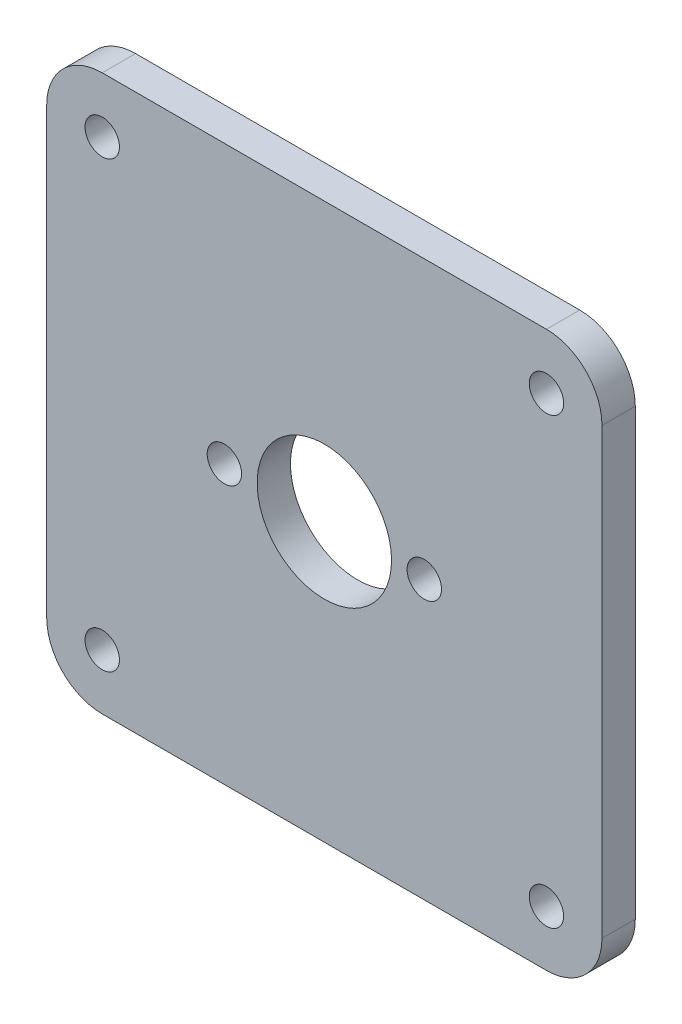
SolidWorks part; units mm, degrees
ref_plane "正面" through (0, 0, 0) normal (0, 0, 1) x (1, 0, 0)
ref_plane "平面" through (0, 0, 0) normal (0, 1, 0) x (1, 0, 0)
ref_plane "右側面" through (0, 0, 0) normal (1, 0, 0) x (0, 0, -1)
sketch "ｽｹｯﾁ1" plane through (0, 0, 0) normal (0, 0, 1) x (1, 0, 0)
  line L0 (0, 25) -> (0, -25) construction
  line L1 (-25, 25) -> (25, 25)
  line L2 (-25, 25) -> (-25, -25)
  line L3 (-25, -25) -> (25, -25)
  line L4 (25, 25) -> (25, -25)
  line L5 (-25, 25) -> (25, -25) construction
  line L6 (-25, -25) -> (25, 25) construction
  line L7 (0, 0) -> (-9, 0) construction
  circle A0 centre (-20, 20) radius 1.55
  circle A1 centre (20, 20) radius 1.55
  circle A2 centre (20, -20) radius 1.55
  circle A3 centre (-20, -20) radius 1.55
  circle A4 centre (0, 0) radius 6.05
  circle A5 centre (-9, 0) radius 1.55
  circle A6 centre (9, 0) radius 1.55
  point P0 (0, 0)
  dimension "D2" = 4
  dimension "D4" = 3.1
  dimension "D5" = 12.1
  dimension "D6" = 3.1
  dimension "D1" = 50
  dimension "D3" = 40
  dimension "D7" = 9
extrude "ﾎﾞｽ - 押し出し1" add sketch "ｽｹｯﾁ1" along normal blind 3
fillet "ﾌｨﾚｯﾄ1" radius 5 4 edges at (-25, -25, 1.5) (25, -25, 1.5) (25, 25, 1.5) (-25, 25, 1.5)
